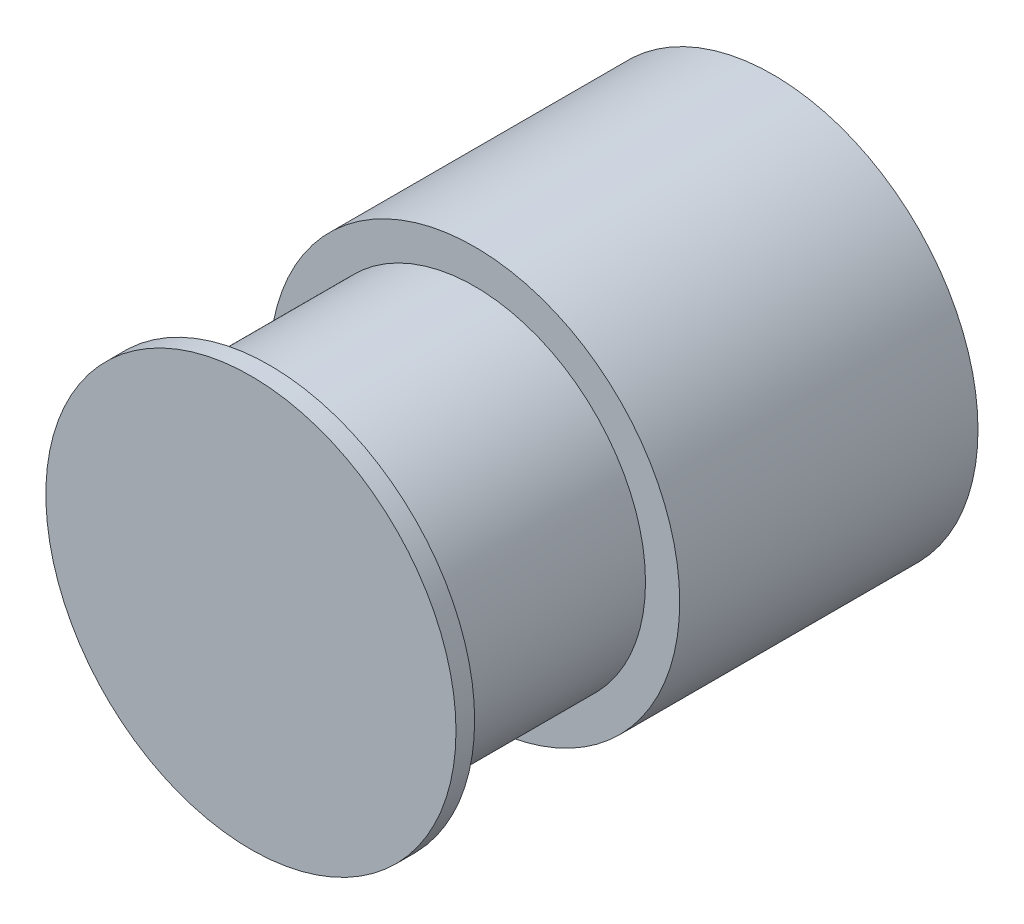
SolidWorks part; units mm, degrees
ref_plane "前视基准面" through (0, 0, 0) normal (0, 0, 1) x (1, 0, 0)
ref_plane "上视基准面" through (0, 0, 0) normal (0, 1, 0) x (1, 0, 0)
ref_plane "右视基准面" through (0, 0, 0) normal (1, 0, 0) x (0, 0, -1)
sketch "草图1" plane through (0, 0, 0) normal (0, 0, 1) x (1, 0, 0)
  circle A0 centre (0, 0) radius 11
  circle A1 centre (0, 0) radius 2.5
  dimension "D1" = 22
  dimension "D2" = 5
extrude "凸台-拉伸1" add sketch "草图1" along normal blind 16
sketch "草图2" plane through (0, 0, 16) normal (0, 0, 1) x (1, 0, 0)
  circle A0 centre (0, 0) radius 9.165
  dimension "D1" = 18.33
extrude "凸台-拉伸2" add sketch "草图2" along normal blind 11
sketch "草图3" plane through (0, 0, 27) normal (0, 0, 1) x (1, 0, 0)
  circle A0 centre (0, 0) radius 11
  dimension "D1" = 22
extrude "凸台-拉伸3" add sketch "草图3" along normal blind 1
